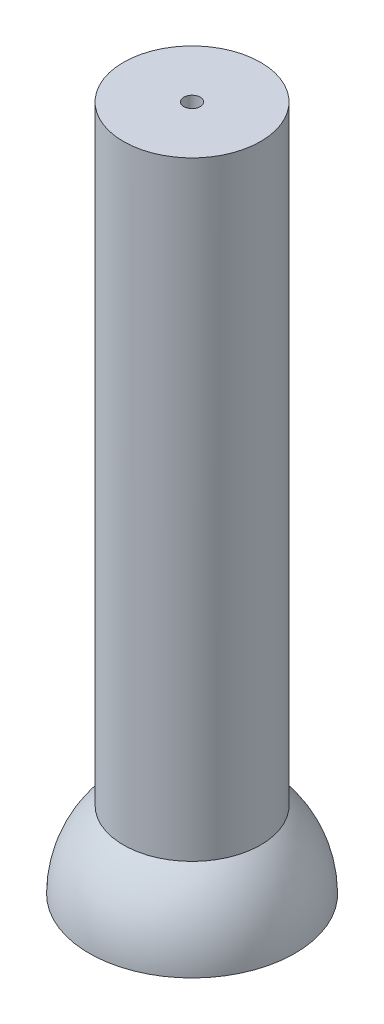
SolidWorks part; units mm, degrees
ref_plane "Front Plane" through (0, 0, 0) normal (0, 0, 1) x (1, 0, 0)
ref_plane "Top Plane" through (0, 0, 0) normal (0, 1, 0) x (1, 0, 0)
ref_plane "Right Plane" through (0, 0, 0) normal (1, 0, 0) x (0, 0, -1)
sketch "Sketch3" plane through (0, 0, 0) normal (0, 1, 0) x (1, 0, 0)
  line L0 (-7.5, 0) -> (7.5, 0) construction
  line L1 (-7.5, 0) -> (7.5, 0)
  arc A0 (-7.5, 0) -> (7.5, 0) centre (0, 0) ccw
  dimension "D1" = 15
revolve "Circular Base" add sketch "Sketch3" angle 180 about L0
sketch "Ciylindrical Support" plane through (0, 0, 0) normal (0, 1, 0) x (1, 0, 0)
  circle A0 centre (0, 0) radius 5
  dimension "D1" = 10
extrude "Cylindrical Support" add sketch "Ciylindrical Support" along normal blind 50
sketch "Sketch5" plane through (0, 50, 0) normal (0, 1, 0) x (1, 0, 0)
  circle A0 centre (0, 0) radius 0.6
  dimension "D1" = 1.2
extrude "Pilot Hole" cut sketch "Sketch5" against normal blind 5
sketch "Sketch6" plane through (0, 0, 0) normal (0, -1, 0) x (1, 0, 0)
  circle A0 centre (0, 0) radius 0.895
  dimension "D1" = 1.79
extrude "Bottom Hole" cut sketch "Sketch6" against normal blind 33
